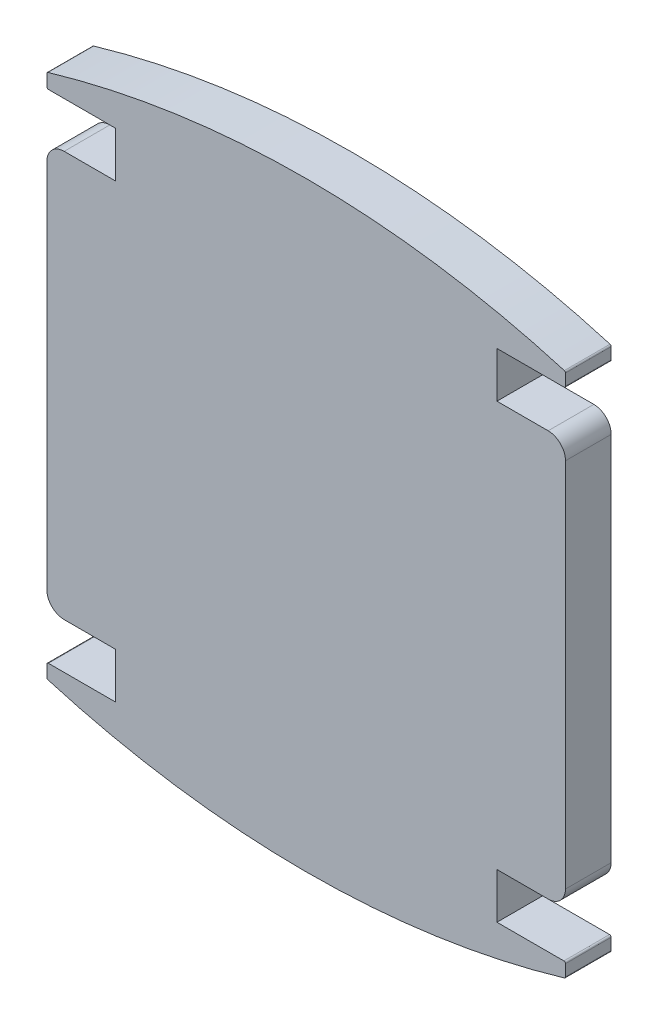
SolidWorks part; units mm, degrees
ref_plane "前视基准面" through (0, 0, 0) normal (0, 0, 1) x (1, 0, 0)
ref_plane "上视基准面" through (0, 0, 0) normal (0, 1, 0) x (1, 0, 0)
ref_plane "右视基准面" through (0, 0, 0) normal (1, 0, 0) x (0, 0, -1)
sketch "草图1" plane through (0, 0, 0) normal (0, 0, 1) x (1, 0, 0)
  line L0 (8.35, 10.875) -> (11.28, 10.875)
  line L1 (11.35, 10.945) -> (11.35, 11.445)
  line L2 (-11.35, 11.445) -> (-11.35, 10.945)
  line L3 (-11.28, 10.875) -> (-8.35, 10.875)
  line L4 (-8.35, 10.875) -> (-8.35, 8.875)
  line L5 (-8.35, 8.875) -> (-10.5916, 8.875)
  line L6 (-11.35, 8.1166) -> (-11.35, -8.1166)
  line L7 (-10.5916, -8.875) -> (-8.35, -8.875)
  line L8 (-8.35, -8.875) -> (-8.35, -10.875)
  line L9 (-11.28, -10.875) -> (-8.35, -10.875)
  line L10 (-11.35, -11.445) -> (-11.35, -10.945)
  line L11 (11.35, -10.945) -> (11.35, -11.445)
  line L12 (8.35, -10.875) -> (11.28, -10.875)
  line L13 (8.35, -10.875) -> (8.35, -8.875)
  line L14 (8.35, -8.875) -> (10.5916, -8.875)
  line L15 (11.35, -8.1166) -> (11.35, 8.1166)
  line L16 (10.5916, 8.875) -> (8.35, 8.875)
  line L17 (8.35, 8.875) -> (8.35, 10.875)
  line L18 (-11.35, 0) -> (11.35, 0) construction
  line L19 (0, 13.1414) -> (0, -13.1414) construction
  arc A0 (11.28, 10.875) -> (11.35, 10.945) centre (11.28, 10.945) ccw
  arc A1 (11.35, 11.445) -> (11.2998, 11.5121) centre (11.28, 11.445) ccw
  arc A2 (11.2998, 11.5121) -> (-11.2998, 11.5121) centre (0, -26.8586) ccw
  arc A3 (-11.2998, 11.5121) -> (-11.35, 11.445) centre (-11.28, 11.445) ccw
  arc A4 (-11.35, 10.945) -> (-11.28, 10.875) centre (-11.28, 10.945) ccw
  arc A5 (-10.5916, 8.875) -> (-11.35, 8.1166) centre (-10.5916, 8.1166) ccw
  arc A6 (-11.35, -8.1166) -> (-10.5916, -8.875) centre (-10.5916, -8.1166) ccw
  arc A7 (-11.35, -10.945) -> (-11.28, -10.875) centre (-11.28, -10.945) cw
  arc A8 (-11.2998, -11.5121) -> (-11.35, -11.445) centre (-11.28, -11.445) cw
  arc A9 (11.2998, -11.5121) -> (-11.2998, -11.5121) centre (0, 26.8586) cw
  arc A10 (11.35, -11.445) -> (11.2998, -11.5121) centre (11.28, -11.445) cw
  arc A11 (11.28, -10.875) -> (11.35, -10.945) centre (11.28, -10.945) cw
  arc A12 (10.5916, -8.875) -> (11.35, -8.1166) centre (10.5916, -8.1166) ccw
  arc A13 (11.35, 8.1166) -> (10.5916, 8.875) centre (10.5916, 8.1166) ccw
  dimension "D4" = 0.7584
  dimension "D6" = 40
  dimension "D7" = 0.07
  dimension "D1" = 17.75
  dimension "D2" = 16.7
  dimension "D3" = 22.7
  dimension "D5" = 2
  dimension "D8" = 0.5
extrude "凸台-拉伸1" add sketch "草图1" along normal blind 2
